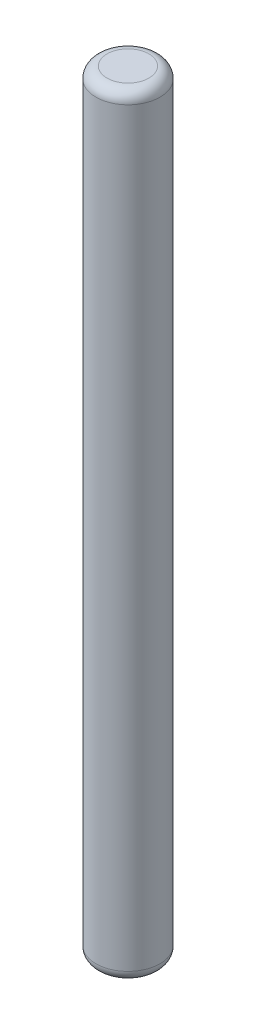
SolidWorks part; units mm, degrees
ref_plane "Ebene vorne" through (0, 0, 0) normal (0, 0, 1) x (1, 0, 0)
ref_plane "Ebene oben" through (0, 0, 0) normal (0, 1, 0) x (1, 0, 0)
ref_plane "Ebene rechts" through (0, 0, 0) normal (1, 0, 0) x (0, 0, -1)
sketch "Skizze1" plane through (0, 0, 0) normal (0, 1, 0) x (1, 0, 0)
  circle A0 centre (0, 0) radius 1.45
extrude "Aufsatz-Linear austragen1" add sketch "Skizze1" along normal blind 35 contours A0
fillet "Verrundung1" radius 0.5 2 edges at (0, 35, 1.45) (0, 0, 1.45)
